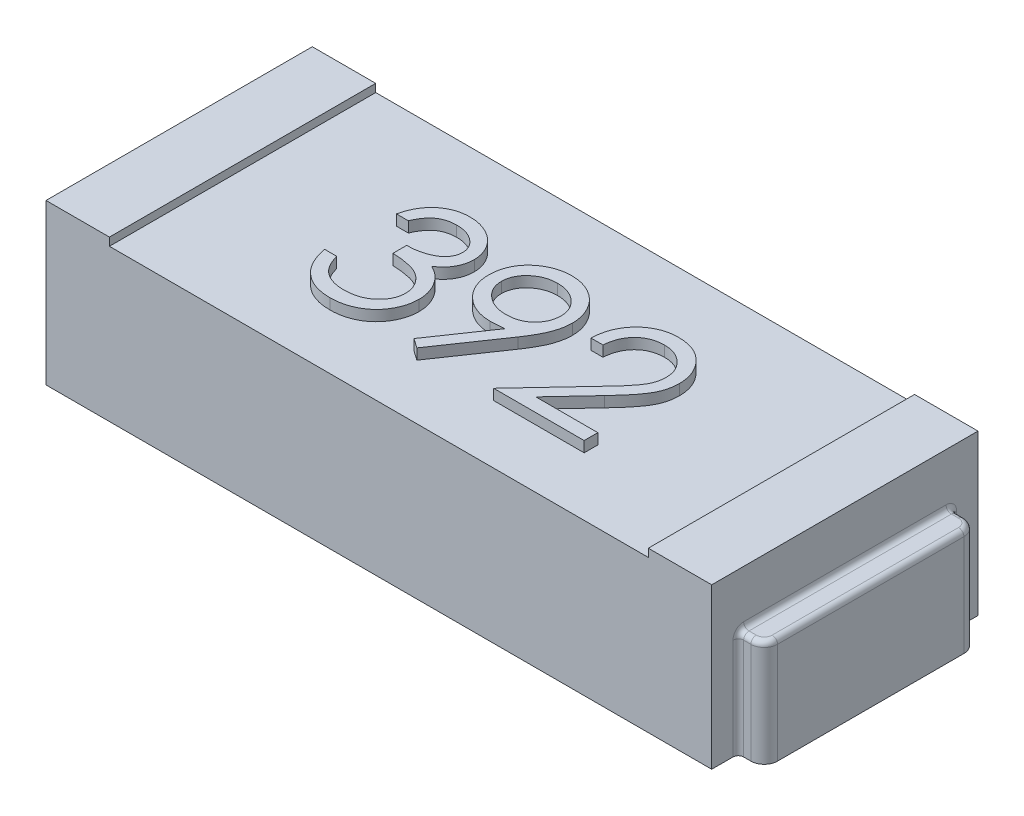
SolidWorks part; units mm, degrees
ref_plane "Plan de face" through (0, 0, 0) normal (0, 0, 1) x (1, 0, 0)
ref_plane "Plan de dessus" through (0, 0, 0) normal (0, 1, 0) x (1, 0, 0)
ref_plane "Plan de droite" through (0, 0, 0) normal (1, 0, 0) x (0, 0, -1)
sketch "Esquisse1" plane through (0, 0, 0) normal (0, 1, 0) x (1, 0, 0)
  line L1 (1.25, -0.5) -> (-1.25, -0.5)
  line L2 (1.25, -0.5) -> (1.25, 0.5)
  line L3 (1.25, 0.5) -> (-1.25, 0.5)
  line L4 (-1.25, -0.5) -> (-1.25, 0.5)
  line L5 (1.25, -0.5) -> (-1.25, 0.5) construction
  line L6 (1.25, 0.5) -> (-1.25, -0.5) construction
  point P0 (0, 0)
  dimension "D1" = 2.5
  dimension "D2" = 1
extrude "Boss.-Extru.1" add sketch "Esquisse1" along normal blind 0.6
sketch "Esquisse2" plane through (0, 0.6, 0) normal (0, 1, 0) x (1, 0, 0)
  line L0 (1.25, 0.5) -> (-1.25, 0.5) construction
  line L1 (1.0118, -0.5) -> (-1.0118, -0.5)
  line L2 (1.0118, -0.5) -> (1.0118, 0.5)
  line L3 (1.0118, 0.5) -> (-1.0118, 0.5)
  line L4 (-1.0118, -0.5) -> (-1.0118, 0.5)
  line L5 (1.0118, -0.5) -> (-1.0118, 0.5) construction
  line L6 (1.0118, 0.5) -> (-1.0118, -0.5) construction
  point P0 (0, 0)
extrude "Enlèv. mat.-Extru.1" cut sketch "Esquisse2" against normal blind 0.03
sketch "Esquisse3" plane through (0, 0, 0) normal (0, 1, 0) x (1, 0, 0)
  line L0 (1.25, -0.5) -> (1.25, 0.5) construction
  line L1 (1.25, 0.4) -> (1.2971, 0.4)
  line L2 (1.25, 0.4) -> (1.25, -0.4)
  line L3 (1.25, -0.4) -> (1.2971, -0.4)
  line L4 (1.3471, 0.35) -> (1.3471, -0.35)
  line L5 (1.25, 0.5) -> (1.0118, 0.5) construction
  line L6 (1.0118, -0.5) -> (1.25, -0.5) construction
  arc A0 (1.2971, -0.4) -> (1.3471, -0.35) centre (1.2971, -0.35) ccw
  arc A1 (1.2971, 0.4) -> (1.3471, 0.35) centre (1.2971, 0.35) cw
  dimension "D1" = 0.05
  dimension "D2" = 0.1
  dimension "D3" = 0.1
extrude "Boss.-Extru.2" add sketch "Esquisse3" along normal blind 0.4
fillet "Congé1" radius 0.02 8 edges at (1.25, 0.2, -0.4) (1.25, 0.2, 0.4) (1.2736, 0.4, -0.4) (1.3325, 0.4, -0.3854) (1.3471, 0.4, 0) (1.3325, 0.4, 0.3854) (1.2736, 0.4, 0.4) (1.25, 0.4, 0)
mirror "Symétrie2" about plane through (0, 0, 0) normal (1, 0, 0) of "Congé1", "Boss.-Extru.2"
sketch "Esquisse4" plane through (0, 0.57, 0) normal (0, 1, 0) x (1, 0, 0)
  line L0 (0.7576, -0.2803) -> (-0.7576, -0.2803) construction
  text T0 "392\r\n" font "Century Gothic" height 0.5
  point P3 (0, -0.2803)
extrude "Boss.-Extru.3" add sketch "Esquisse4" along normal blind 0.04
